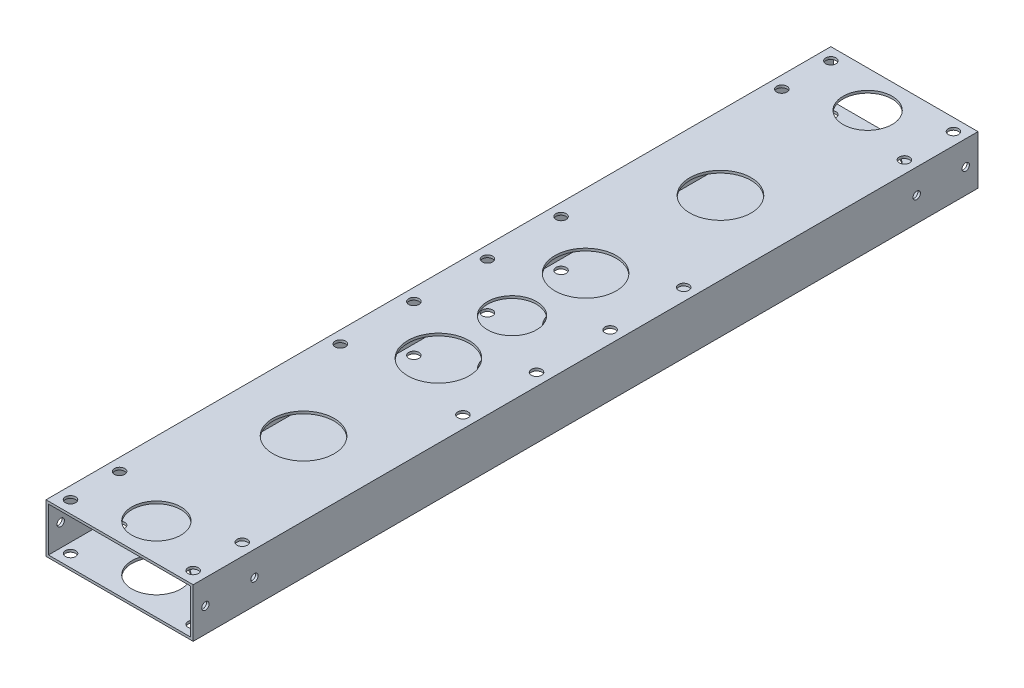
SolidWorks part; units mm, degrees
ref_plane "前视基准面" through (0, 0, 0) normal (0, 0, 1) x (1, 0, 0)
ref_plane "上视基准面" through (0, 0, 0) normal (0, 1, 0) x (1, 0, 0)
ref_plane "右视基准面" through (0, 0, 0) normal (1, 0, 0) x (0, 0, -1)
sketch "草图1" plane through (0, 0, 0) normal (0, 0, 1) x (1, 0, 0)
  line L1 (0, 0) -> (60, 0)
  line L2 (0, 0) -> (0, 20)
  line L3 (0, 20) -> (60, 20)
  line L4 (60, 0) -> (60, 20)
  dimension "D1" = 60
  dimension "D2" = 20
extrude "拉伸-薄壁1" add sketch "草图1" along normal blind 320 thin thin type one direction reverse wall 1
sketch "草图2" plane through (0, 20, 0) normal (0, 1, 0) x (1, 0, 0)
  line L0 (0, -160) -> (60, -160) construction
  line L1 (0, -320) -> (0, 0) construction
  line L2 (60, -320) -> (60, 0) construction
  line L3 (5, -145) -> (5, -175) construction
  line L4 (30, 0) -> (30, -320) construction
  line L5 (60, 0) -> (0, 0) construction
  line L6 (60, -320) -> (0, -320) construction
  line L7 (55, -145) -> (55, -175) construction
  line L8 (5, -315) -> (55, -295) construction
  line L10 (5, -25) -> (55, -25) construction
  line L11 (5, -25) -> (5, -5) construction
  line L12 (5, -5) -> (55, -5) construction
  line L13 (55, -25) -> (55, -5) construction
  line L14 (5, -25) -> (55, -5) construction
  line L15 (5, -5) -> (55, -25) construction
  line L16 (5, -295) -> (55, -315) construction
  line L17 (55, -295) -> (55, -315) construction
  line L18 (5, -315) -> (55, -315) construction
  line L19 (5, -295) -> (5, -315) construction
  line L20 (5, -295) -> (55, -295) construction
  circle A0 centre (5, -145) radius 2.1
  circle A1 centre (5, -175) radius 2.1
  circle A2 centre (55, -175) radius 2.1
  circle A3 centre (55, -145) radius 2.1
  circle A4 centre (5, -115) radius 2.1
  circle A5 centre (5, -205) radius 2.1
  circle A6 centre (55, -205) radius 2.1
  circle A7 centre (55, -115) radius 2.1
  circle A8 centre (5, -5) radius 2.1
  circle A9 centre (55, -5) radius 2.1
  circle A10 centre (55, -25) radius 2.1
  circle A11 centre (5, -25) radius 2.1
  circle A12 centre (5, -295) radius 2.1
  circle A13 centre (55, -295) radius 2.1
  circle A14 centre (55, -315) radius 2.1
  circle A15 centre (5, -315) radius 2.1
  point P14 (5, -160)
  point P23 (30, -15)
  point P46 (30, -305)
  dimension "D3" = 4.2
  dimension "D4" = 4.2
  dimension "D6" = 5
  dimension "D9" = 4.2
  dimension "D1" = 30
  dimension "D2" = 5
  dimension "D5" = 90
  dimension "D7" = 5
  dimension "D8" = 20
extrude "切除-拉伸1" cut sketch "草图2" against normal through all
sketch "草图4" plane through (60, 0, 0) normal (1, 0, 0) x (0, 0, -1)
  line L0 (-320, 10) -> (0, 10) construction
  line L1 (-320, 0) -> (-320, 20) construction
  line L2 (0, 0) -> (0, 20) construction
  line L3 (-160, 20) -> (-160, 0) construction
  line L4 (-320, 20) -> (0, 20) construction
  line L5 (-320, 0) -> (0, 0) construction
  circle A0 centre (-315, 10) radius 1.5
  circle A1 centre (-295, 10) radius 1.5
  circle A2 centre (-25, 10) radius 1.5
  circle A3 centre (-5, 10) radius 1.5
  dimension "D1" = 5
  dimension "D3" = 3
  dimension "D2" = 20
extrude "切除-拉伸2" cut sketch "草图4" against normal through all
sketch "草图5" plane through (0, 20, 0) normal (0, 1, 0) x (1, 0, 0)
  line L0 (0, -160) -> (60, -160) construction
  line L1 (0, -320) -> (0, 0) construction
  line L2 (60, -320) -> (60, 0) construction
  circle A0 centre (30, -160) radius 10
  circle A1 centre (30, -130) radius 12.5
  circle A2 centre (30, -190) radius 12.5
  circle A3 centre (30, -75) radius 12.5
  circle A4 centre (30, -15) radius 10
  circle A5 centre (30, -305) radius 10
  circle A6 centre (30, -245) radius 12.5
  dimension "D1" = 20
  dimension "D2" = 25
  dimension "D4" = 85
  dimension "D5" = 25
  dimension "D6" = 145
  dimension "D7" = 20
  dimension "D3" = 30
extrude "切除-拉伸3" cut sketch "草图5" against normal through all
